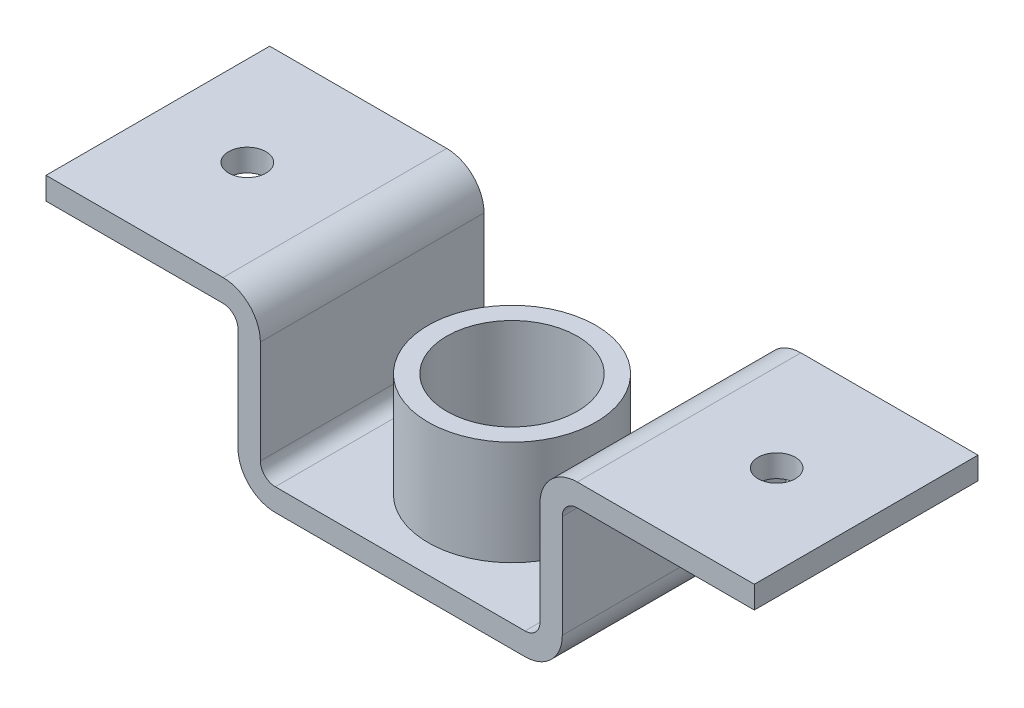
SolidWorks part; units mm, degrees
ref_plane "Front Plane" through (0, 0, 0) normal (0, 0, 1) x (1, 0, 0)
ref_plane "Top Plane" through (0, 0, 0) normal (0, 1, 0) x (1, 0, 0)
ref_plane "Right Plane" through (0, 0, 0) normal (1, 0, 0) x (0, 0, -1)
sketch "Sketch1" plane through (0, 0, 0) normal (0, 0, 1) x (1, 0, 0)
  line L0 (0, 0) -> (237.5, 0)
  line L1 (287.5, -50) -> (287.5, -188)
  line L2 (307.5, -208) -> (642.5, -208)
  line L3 (662.5, -188) -> (662.5, -50)
  line L4 (712.5, 0) -> (950, 0)
  line L5 (0, -30) -> (237.5, -30)
  line L6 (257.5, -50) -> (257.5, -188)
  line L7 (307.5, -238) -> (642.5, -238)
  line L8 (692.5, -188) -> (692.5, -50)
  line L9 (712.5, -30) -> (950, -30)
  line L10 (0, -30) -> (0, 0)
  line L11 (950, -30) -> (950, 0)
  line L12 (257.5, -30) -> (257.5, -238) construction
  line L13 (257.5, -238) -> (692.5, -238) construction
  line L14 (692.5, -238) -> (692.5, -30) construction
  line L15 (662.5, -208) -> (662.5, 0) construction
  line L16 (662.5, 0) -> (950, 0) construction
  line L17 (0, 0) -> (287.5, 0) construction
  line L18 (287.5, 0) -> (287.5, -208) construction
  line L19 (692.5, -30) -> (950, -30) construction
  line L20 (287.5, -208) -> (662.5, -208) construction
  line L21 (0, -30) -> (257.5, -30) construction
  arc A0 (257.5, -188) -> (307.5, -238) centre (307.5, -188) ccw
  arc A1 (642.5, -238) -> (692.5, -188) centre (642.5, -188) ccw
  arc A2 (662.5, -50) -> (712.5, 0) centre (712.5, -50) cw
  arc A3 (237.5, 0) -> (287.5, -50) centre (237.5, -50) cw
  arc A4 (692.5, -50) -> (712.5, -30) centre (712.5, -50) cw
  arc A5 (642.5, -208) -> (662.5, -188) centre (642.5, -188) ccw
  arc A6 (287.5, -188) -> (307.5, -208) centre (307.5, -188) ccw
  arc A7 (237.5, -30) -> (257.5, -50) centre (237.5, -50) cw
  point P25 (0, 0)
  dimension "D5" = 50
  dimension "D6" = 20
  dimension "D1" = 375
  dimension "D2" = 950
  dimension "D3" = 208
  dimension "D4" = 30
extrude "Boss-Extrude1" add sketch "Sketch1" along normal blind 300
sketch "Sketch2" plane through (0, -208, 0) normal (0, 1, 0) x (1, 0, 0)
  line L0 (475, -150) -> (475, 0) construction
  line L1 (642.5, 0) -> (307.5, 0) construction
  circle A0 centre (475, -150) radius 112.5
  circle A1 centre (475, -150) radius 87.5
  point P3 (475, -144.3881)
  dimension "D1" = 225
  dimension "D2" = 175
  dimension "D3" = 150
extrude "Boss-Extrude2" add sketch "Sketch2" along normal blind 170 from surface at -30 starting at face at (475, -238, 150)
sketch "Sketch3" plane through (0, -238, 0) normal (0, -1, 0) x (1, 0, 0)
  line L0 (475, 300) -> (475, 0) construction
  line L1 (307.5, 300) -> (642.5, 300) construction
  line L2 (307.5, 0) -> (642.5, 0) construction
  line L3 (950, 300) -> (950, 0) construction
  line L4 (712.5, 300) -> (950, 300) construction
  circle A0 centre (475, 150) radius 37.5
  circle A1 centre (830, 150) radius 25
  circle A2 centre (120, 150) radius 25
  dimension "D1" = 75
  dimension "D4" = 50
  dimension "D2" = 120
  dimension "D3" = 150
extrude "Cut-Extrude1" cut sketch "Sketch3" against normal through all
